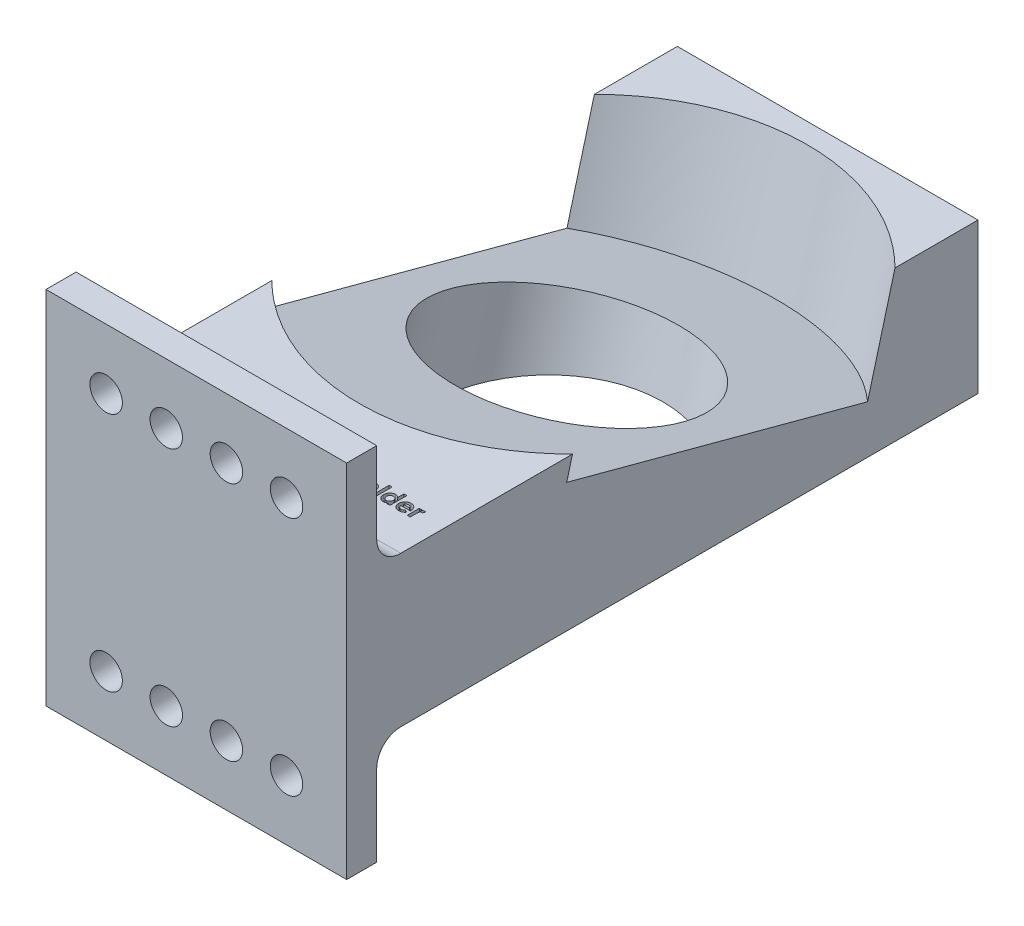
SolidWorks part; units mm, degrees
ref_plane "Front Plane" through (0, 0, 0) normal (0, 0, 1) x (1, 0, 0)
ref_plane "Top Plane" through (0, 0, 0) normal (0, 1, 0) x (1, 0, 0)
ref_plane "Right Plane" through (0, 0, 0) normal (1, 0, 0) x (0, 0, -1)
sketch "Sketch1" plane through (0, 0, 0) normal (1, 0, 0) x (0, 0, -1)
  line L1 (63.5, 15.875) -> (-63.5, 15.875)
  line L2 (63.5, 15.875) -> (63.5, -15.875)
  line L3 (63.5, -15.875) -> (-63.5, -15.875)
  line L4 (-63.5, 15.875) -> (-63.5, -15.875)
  line L5 (63.5, 15.875) -> (-63.5, -15.875) construction
  line L6 (63.5, -15.875) -> (-63.5, 15.875) construction
  point P0 (0, 0)
  dimension "D1" = 31.75
  dimension "D2" = 127
extrude "Boss-Extrude1" add sketch "Sketch1" along normal mid plane 63.5
sketch "Sketch2" plane through (0, 0, 0) normal (1, 0, 0) x (0, 0, -1)
  line L0 (0, -28.575) -> (18.5919, 40.8109) construction
  line L1 (0, 0) -> (0, -41.4309) construction
  line L3 (32.0221, -3.5248) -> (23.6145, -34.9025)
  line L4 (23.6145, -34.9025) -> (0, -28.575)
  line L5 (0, -28.575) -> (16.956, 34.7058)
  line L8 (63.5, -15.875) -> (63.5, 15.875) construction
  line L9 (-63.5, -15.875) -> (63.5, -15.875) construction
  line L10 (32.0221, -3.5248) -> (52.5698, -9.0305)
  line L11 (52.5698, -9.0305) -> (61.1182, 22.8726)
  line L12 (61.1182, 22.8726) -> (16.956, 34.7058)
  point P7 (73.8501, 22.9919)
  point P11 (65.2273, -9.1888)
  point P12 (29.656, 34.7058)
  dimension "D1" = 15
  dimension "D2" = 48.895
  dimension "D3" = 63.5
  dimension "D4" = 12.7
  dimension "D5" = 91.44
  dimension "D6" = 33.0285
  dimension "D7" = 32.4846
revolve "Cut-Revolve1" cut sketch "Sketch2" angle 360 about L0
sketch "Sketch3" plane through (0, 0, 63.5) normal (0, 0, 1) x (1, 0, 0)
  line L0 (31.75, 15.875) -> (31.75, -15.875) construction
  line L1 (-31.75, -38.1) -> (31.75, -38.1)
  line L2 (-31.75, -38.1) -> (-31.75, 38.1)
  line L3 (-31.75, 38.1) -> (31.75, 38.1)
  line L4 (31.75, -38.1) -> (31.75, 38.1)
  line L5 (-31.75, -38.1) -> (31.75, 38.1) construction
  line L6 (-31.75, 38.1) -> (31.75, -38.1) construction
  circle A0 centre (-19.05, 25.4) radius 3.429
  circle A1 centre (-6.35, 25.4) radius 3.429
  circle A2 centre (6.35, 25.4) radius 3.429
  circle A3 centre (19.05, 25.4) radius 3.429
  circle A4 centre (-6.35, -25.4) radius 3.429
  circle A5 centre (6.35, -25.4) radius 3.429
  circle A6 centre (19.05, -25.4) radius 3.429
  circle A7 centre (-19.05, -25.4) radius 3.429
  point P0 (0, 0)
  dimension "D2" = 6.858
  dimension "D1" = 76.2
  dimension "D3" = 12.7
  dimension "D4" = 12.7
  dimension "D5" = 4
  dimension "D6" = 2
extrude "Boss-Extrude2" add sketch "Sketch3" along normal blind 6.35
fillet "Fillet1" radius 5.08 2 edges at (0, 15.875, 63.5) (0, -15.875, 63.5)
sketch "Sketch4" plane through (0, 15.875, 0) normal (0, 1, 0) x (1, 0, 0)
  line L0 (-31.75, -50.8) -> (31.75, -50.8) construction
  line L1 (-31.75, -22.1478) -> (-31.75, -58.42) construction
  line L2 (31.75, -22.1478) -> (31.75, -58.42) construction
  line L3 (31.75, -69.85) -> (-31.75, -69.85) construction
  text T0 "<b>300 kHz Sangjin Holder</b>"
  dimension "D1" = 19.05
extrude "Cut-Extrude1" cut sketch "Sketch4" against normal blind 2.54
